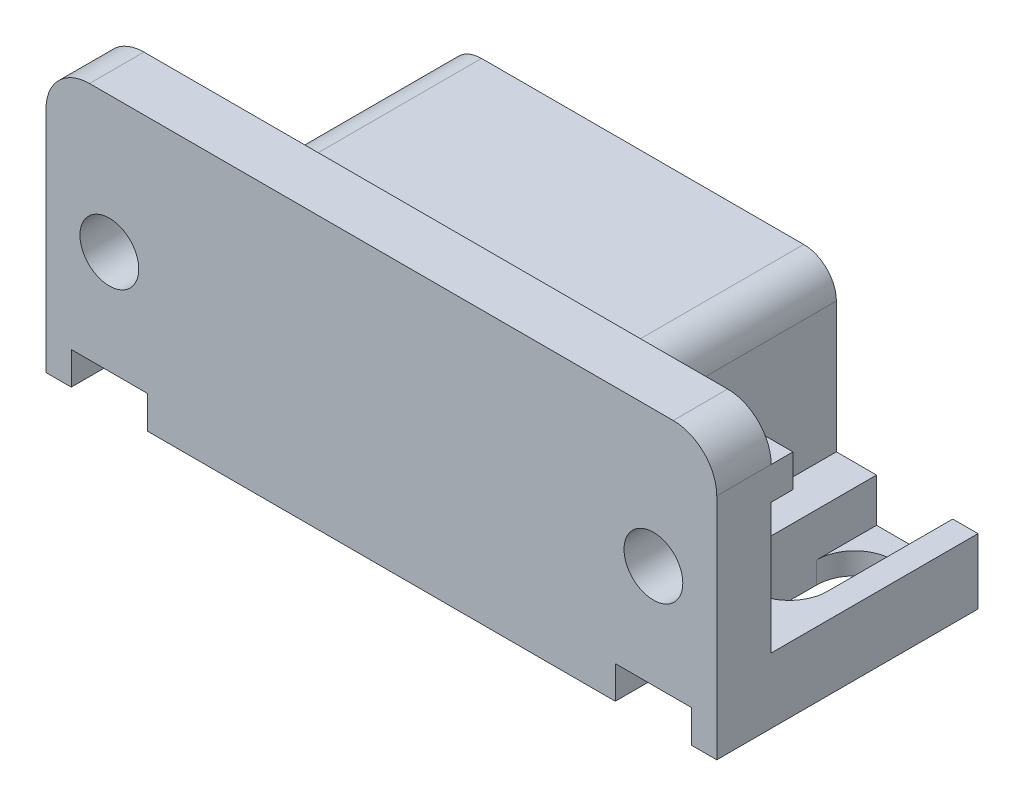
SolidWorks part; units mm, degrees
material "ABS"
ref_plane "Plano frontal" through (0, 0, 0) normal (0, 0, 1) x (1, 0, 0)
ref_plane "Plano superior" through (0, 0, 0) normal (0, 1, 0) x (1, 0, 0)
ref_plane "Plano direito" through (0, 0, 0) normal (1, 0, 0) x (0, 0, -1)
sketch "Esboço1" plane through (0, 0, 0) normal (0, 0, 1) x (1, 0, 0)
  line L0 (-13.405, 6.25) -> (13.405, 6.25)
  line L1 (15.405, 4.25) -> (15.405, -6.25)
  line L2 (15.405, -6.25) -> (-15.405, -6.25)
  line L3 (-15.405, -6.25) -> (-15.405, 4.25)
  line L4 (0, 0) -> (0, -6.25) construction
  arc A0 (13.405, 6.25) -> (15.405, 4.25) centre (13.405, 4.25) cw
  arc A1 (-15.405, 4.25) -> (-13.405, 6.25) centre (-13.405, 4.25) cw
  dimension "D2" = 2
  dimension "D3" = 2
  dimension "D1" = 12.5
  dimension "D4" = 30.81
  dimension "D5" = 6.25
extrude "Ressalto-extrusão1" add sketch "Esboço1" against normal blind 2.5
sketch "Esboço2" plane through (0, 0, -2.5) normal (0, 0, -1) x (-1, 0, 0)
  line L0 (15.405, 4.25) -> (15.405, -6.25) construction
  line L1 (-15.405, -6.25) -> (15.405, -6.25)
  line L2 (-15.405, -6.25) -> (-15.405, -3.25)
  line L3 (-15.405, -3.25) -> (15.405, -3.25)
  line L4 (15.405, -6.25) -> (15.405, -3.25)
  dimension "D1" = 3
extrude "Ressalto-extrusão2" add sketch "Esboço2" along normal blind 9.5 contours L3 L4 L1 L2
sketch "Esboço3" plane through (0, 0, -12) normal (0, 0, -1) x (-1, 0, 0)
  line L0 (-15.405, -6.25) -> (15.405, -6.25) construction
  line L1 (-8.9, -6.25) -> (8.9, -6.25)
  line L2 (-8.9, -6.25) -> (-8.9, -5.25)
  line L3 (-8.9, -5.25) -> (8.9, -5.25)
  line L4 (8.9, -6.25) -> (8.9, -5.25)
  line L5 (0, -5.25) -> (0, -3.25) construction
  line L6 (-15.405, -3.25) -> (15.405, -3.25) construction
  dimension "D1" = 1
  dimension "D2" = 17.8
extrude "Corte-extrusão1" cut sketch "Esboço3" against normal blind 10
sketch "Esboço4" plane through (0, 0, -2.5) normal (0, 0, -1) x (-1, 0, 0)
  line L1 (-15.405, 2.75) -> (15.405, 2.75)
  line L2 (-15.405, 2.75) -> (-15.405, 4.25)
  line L3 (-15.405, 4.25) -> (15.405, 4.25)
  line L4 (15.405, 2.75) -> (15.405, 4.25)
  line L5 (15.405, 4.25) -> (15.405, -3.25) construction
  line L6 (8.9, -6.25) -> (15.405, -6.25) construction
  dimension "D1" = 1.5
  dimension "D2" = 10.5
  dimension "D3" = 30.81
extrude "Ressalto-extrusão3" add sketch "Esboço4" along normal blind 1
sketch "Esboço5" plane through (0, 0, -2.5) normal (0, 0, -1) x (-1, 0, 0)
  line L0 (8.9, -5.25) -> (-8.9, -5.25) construction
  line L1 (-8.9, -5.25) -> (8.9, -5.25)
  line L2 (-8.9, -5.25) -> (-8.9, 4.25)
  line L3 (-8.9, 4.25) -> (8.9, 4.25)
  line L4 (8.9, -5.25) -> (8.9, 4.25)
  line L5 (15.405, 4.25) -> (-15.405, 4.25) construction
  line L6 (0, 4.25) -> (0, 0) construction
  dimension "D1" = 17.8
extrude "Ressalto-extrusão4" add sketch "Esboço5" along normal up to vertex
fillet "Filete1" radius 1.5 2 edges at (8.9, 4.25, -7.75) (-8.9, 4.25, -7.75)
sketch "Esboço6" plane through (0, -3.25, 0) normal (0, 1, 0) x (1, 0, 0)
  line L0 (12.495, 6.25) -> (12.495, 9.25) construction
  line L1 (10.745, 6.25) -> (10.745, 9.25)
  line L2 (14.245, 6.25) -> (14.245, 9.25)
  line L3 (15.405, 12) -> (8.9, 12) construction
  arc A0 (10.745, 6.25) -> (14.245, 6.25) centre (12.495, 6.25) ccw
  arc A1 (14.245, 9.25) -> (10.745, 9.25) centre (12.495, 9.25) ccw
  point P2 (12.495, 7.75)
  dimension "D1" = 1.75
  dimension "D2" = 3
  dimension "D3" = 12.495
  dimension "D4" = 2.75
extrude "Corte-extrusão2" cut sketch "Esboço6" against normal through all
mirror "Espelhar1" about plane through (0, 0, 0) normal (1, 0, 0) of "Corte-extrusão2"
sketch "Esboço7" plane through (0, -3.25, 0) normal (0, 1, 0) x (1, 0, 0)
  line L0 (10.745, 9.25) -> (10.745, 6.25) construction
  line L1 (10.745, 7.75) -> (14.245, 7.75)
  line L2 (10.745, 7.75) -> (10.745, 12)
  line L3 (10.745, 12) -> (14.245, 12)
  line L4 (14.245, 7.75) -> (14.245, 12)
  line L5 (15.405, 12) -> (8.9, 12) construction
extrude "Corte-extrusão3" cut sketch "Esboço7" against normal blind 2
mirror "Espelhar2" about plane through (0, 0, 0) normal (1, 0, 0) of "Corte-extrusão3"
sketch "Esboço8" plane through (0, -6.25, 0) normal (0, -1, 0) x (1, 0, 0)
  line L0 (-14.245, -6.25) -> (-14.245, -9.25) construction
  line L1 (-14.245, -6.7273) -> (-10.745, -6.7273)
  line L2 (-14.245, -6.7273) -> (-14.245, 0)
  line L3 (-14.245, 0) -> (-10.745, 0)
  line L4 (-10.745, -6.7273) -> (-10.745, 0)
  line L5 (-15.405, 0) -> (15.405, 0) construction
extrude "Corte-extrusão4" cut sketch "Esboço8" against normal blind 1.5
mirror "Espelhar3" about plane through (0, 0, 0) normal (1, 0, 0) of "Corte-extrusão3", "Corte-extrusão4"
sketch "Esboço9" plane through (0, 0, 0) normal (0, 0, 1) x (1, 0, 0)
  line L0 (12.495, 0) -> (0, 0) construction
  circle A0 centre (12.495, 0) radius 1.35
  dimension "D1" = 2.7
  dimension "D2" = 12.495
extrude "Corte-extrusão5" cut sketch "Esboço9" against normal through all
mirror "Espelhar4" about plane through (0, 0, 0) normal (1, 0, 0) of "Corte-extrusão5"
sketch "Esboço10" plane through (0, -5.25, 0) normal (0, -1, 0) x (1, 0, 0)
  line L0 (-8.9, -12) -> (8.9, -12) construction
  line L1 (-0.4, -12) -> (0.4, -12)
  line L2 (-0.4, -12) -> (-0.4, -10)
  line L3 (-0.4, -10) -> (0.4, -10)
  line L4 (0.4, -12) -> (0.4, -10)
  line L5 (0, -10) -> (0, -2) construction
  line L6 (-8.9, -2) -> (8.9, -2) construction
  dimension "D1" = 0.8
  dimension "D2" = 2
extrude "Corte-extrusão6" cut sketch "Esboço10" against normal blind 2.5
pattern_linear "Padrão linear1" count 3 spacing 2.77 along (-1, 0, 0) count 3 spacing 2.77 along (1, 0, 0) of "Corte-extrusão6"
sketch "Esboço11" plane through (0, -5.25, 0) normal (0, -1, 0) x (1, 0, 0)
  line L0 (5.94, -12) -> (8.9, -12) construction
  line L1 (3.755, -12) -> (4.555, -12)
  line L2 (3.755, -12) -> (3.755, -7.3)
  line L3 (3.755, -7.3) -> (4.555, -7.3)
  line L4 (4.555, -12) -> (4.555, -7.3)
  line L7 (5.54, -12) -> (4.155, -12) construction
  line L8 (5.14, -12) -> (5.94, -12) construction
  dimension "D1" = 1.385
  dimension "D2" = 0.8
  dimension "D3" = 4.7
extrude "Corte-extrusão7" cut sketch "Esboço11" against normal blind 1
sketch "Esboço12" plane through (0, 0, -12) normal (0, 0, -1) x (-1, 0, 0)
  line L0 (-3.755, -2.75) -> (-5.94, -2.75) construction
  line L1 (-4.555, -4.25) -> (-3.755, -4.25)
  line L2 (-4.555, -4.25) -> (-4.555, -2.75)
  line L3 (-4.555, -2.75) -> (-3.755, -2.75)
  line L4 (-3.755, -4.25) -> (-3.755, -2.75)
  dimension "D1" = 0.8
extrude "Corte-extrusão8" cut sketch "Esboço12" against normal blind 2
pattern_linear "Padrão linear2" count 4 spacing 2.77 along (-1, 0, 0) of "Corte-extrusão8", "Corte-extrusão7"
